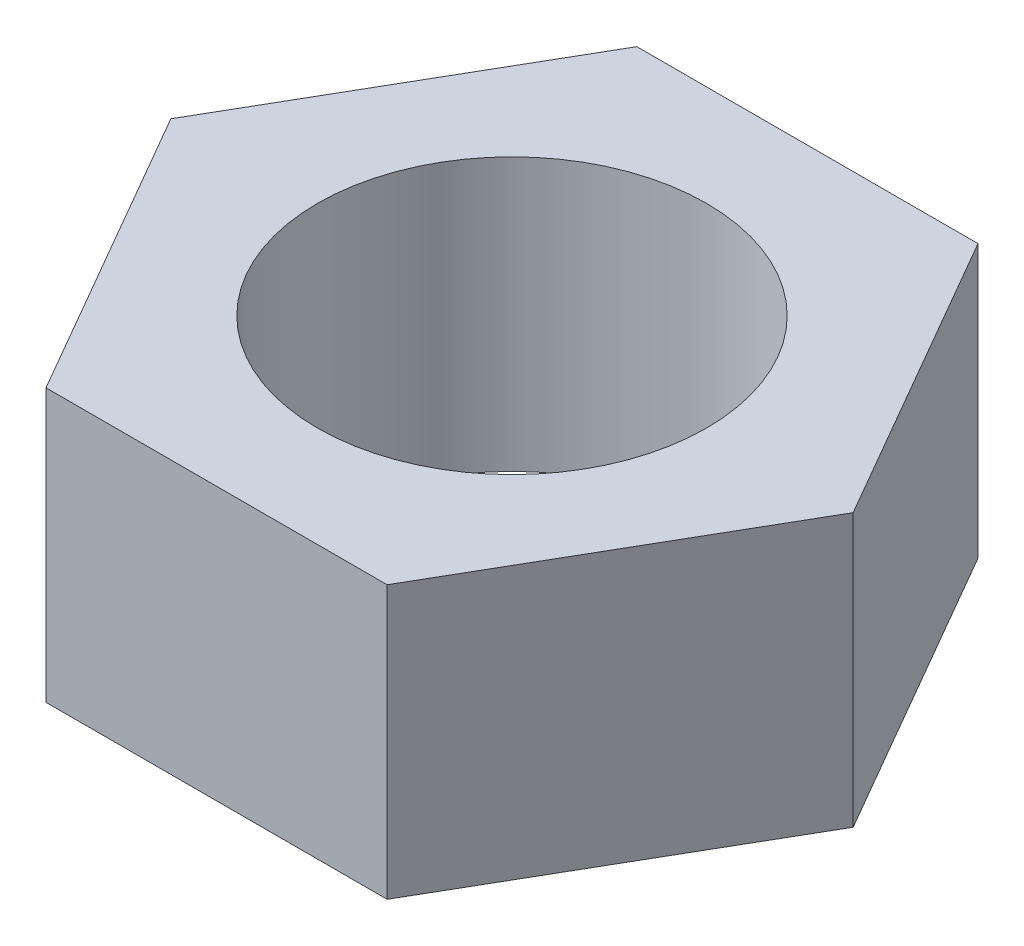
SolidWorks part; units mm, degrees
ref_plane "Front Plane" through (0, 0, 0) normal (0, 0, 1) x (1, 0, 0)
ref_plane "Top Plane" through (0, 0, 0) normal (0, 1, 0) x (1, 0, 0)
ref_plane "Right Plane" through (0, 0, 0) normal (1, 0, 0) x (0, 0, -1)
sketch "Sketch1" plane through (0, 0, 0) normal (0, 1, 0) x (1, 0, 0)
  line L1 (4.8209, -8.35) -> (9.6417, 0)
  line L2 (9.6417, 0) -> (4.8209, 8.35)
  line L3 (4.8209, 8.35) -> (-4.8209, 8.35)
  line L4 (-4.8209, 8.35) -> (-9.6417, 0)
  line L5 (-9.6417, 0) -> (-4.8209, -8.35)
  line L6 (-4.8209, -8.35) -> (4.8209, -8.35)
  circle A0 centre (0, 0) radius 8.35 construction
  circle A1 centre (0, 0) radius 5.5
  dimension "D2" = 11
  dimension "D1" = 16.7
extrude "Boss-Extrude1" add sketch "Sketch1" along normal blind 7.7
